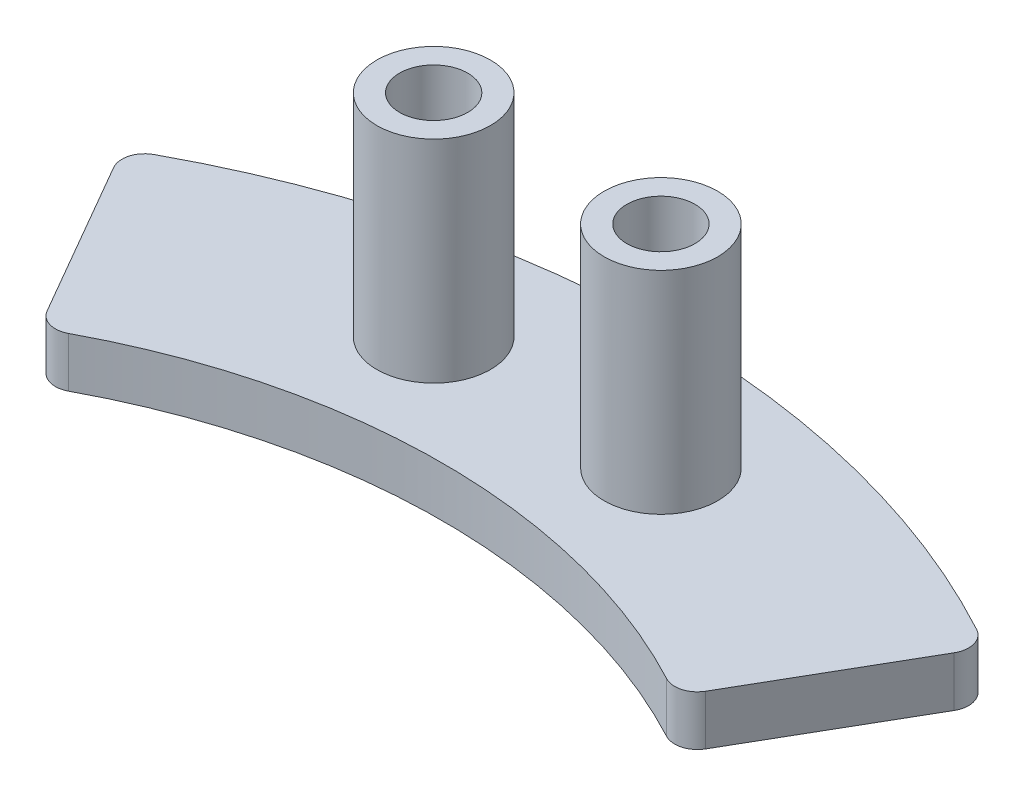
SolidWorks part; units mm, degrees
ref_plane "Front Plane" through (0, 0, 0) normal (0, 0, 1) x (1, 0, 0)
ref_plane "Top Plane" through (0, 0, 0) normal (0, 1, 0) x (1, 0, 0)
ref_plane "Right Plane" through (0, 0, 0) normal (1, 0, 0) x (0, 0, -1)
sketch "Sketch1" plane through (0, 0, 0) normal (0, 1, 0) x (1, 0, 0)
  line L0 (-14, 24.2487) -> (-19, 32.909) construction
  line L1 (14, 24.2487) -> (19, 32.909) construction
  line L2 (0, 0) -> (4, 0) construction
  line L3 (-19, 32.909) -> (-14, 24.2487)
  line L4 (19, 32.909) -> (14, 24.2487)
  circle A0 centre (0, 0) radius 28 construction
  circle A1 centre (0, 0) radius 38 construction
  arc A2 (-19, 32.909) -> (19, 32.909) centre (0, 0) cw
  arc A3 (-14, 24.2487) -> (14, 24.2487) centre (0, 0) cw
  arc A4 (-16.5, 28.5788) -> (16.5, 28.5788) centre (0, 0) cw construction
  dimension "D1" = 76
  dimension "D2" = 56
  dimension "D6" = 60
  dimension "D3" = 60
extrude "Boss-Extrude1" add sketch "Sketch1" along normal blind 2.2
sketch "Sketch2" plane through (0, 2.2, 0) normal (0, 1, 0) x (1, 0, 0)
  line L1 (14, 24.2487) -> (19, 32.909) construction
  line L2 (-5, 32.619) -> (5, 32.619) construction
  line L3 (0, 32.619) -> (0, 0) construction
  line L5 (-19, 32.909) -> (-14, 24.2487) construction
  arc A0 (-16.5, 28.5788) -> (16.5, 28.5788) centre (0, 0) cw construction
  circle A1 centre (-5, 32.619) radius 2.5
  circle A2 centre (5, 32.619) radius 2.5
  dimension "D1" = 5
  dimension "D4" = 33
  dimension "D2" = 10
  dimension "D3" = 32.619
extrude "Boss-Extrude2" add sketch "Sketch2" along normal blind 9.3
sketch "Sketch5" plane through (0, 11.5, 0) normal (0, 1, 0) x (1, 0, 0)
  circle A0 centre (-5, 32.619) radius 1.5
  circle A2 centre (5, 32.619) radius 1.5
  dimension "D1" = 3
extrude "Cut-Extrude1" cut sketch "Sketch5" against normal blind 3.5
sketch "Sketch6" plane through (0, 0, 0) normal (0, -1, 0) x (1, 0, 0)
  line L0 (0, 0) -> (0, -33) construction
  line L1 (-19, -32.909) -> (-14, -24.2487) construction
  line L2 (14, -24.2487) -> (19, -32.909) construction
  arc A0 (-16.5, -28.5788) -> (16.5, -28.5788) centre (0, 0) ccw construction
  circle A1 centre (0, -33) radius 1.5
  dimension "D1" = 3
extrude "Cut-Extrude2" cut sketch "Sketch6" against normal blind 1
fillet "Fillet1" radius 1 4 edges at (19, 1.1, -32.909) (14, 1.1, -24.2487) (-19, 1.1, -32.909) (-14, 1.1, -24.2487)
